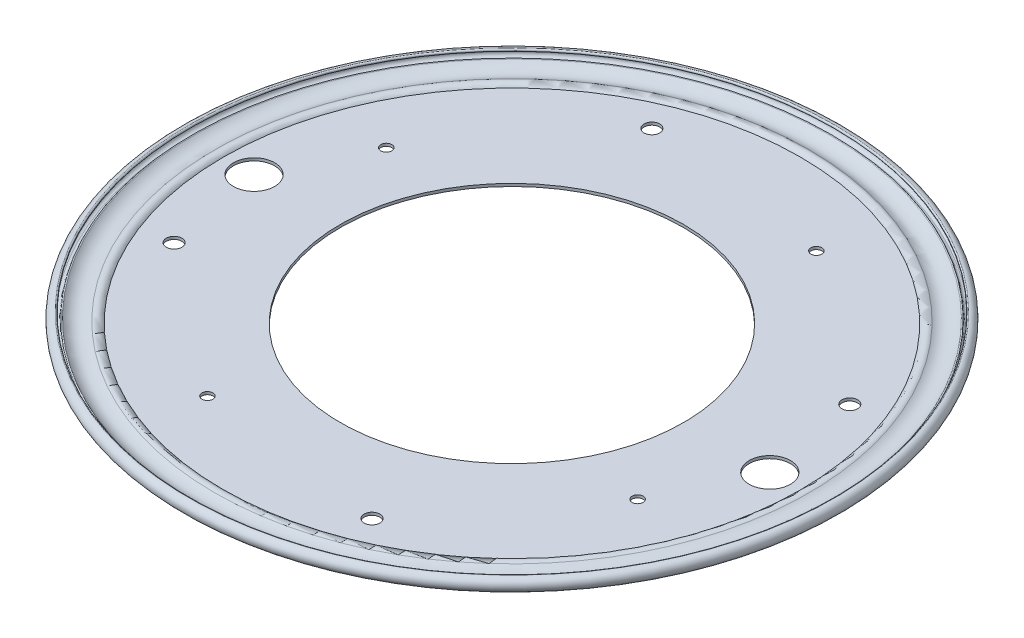
SolidWorks part; units mm, degrees
ref_plane "Front Plane" through (0, 0, 0) normal (0, 0, 1) x (1, 0, 0)
ref_plane "Top Plane" through (0, 0, 0) normal (0, 1, 0) x (1, 0, 0)
ref_plane "Right Plane" through (0, 0, 0) normal (1, 0, 0) x (0, 0, -1)
sketch "Sketch2" plane through (0, 0, 0) normal (1, 0, 0) x (0, 0, -1)
  line L0 (-151.13, 3.048) -> (-152.4, 3.048) construction
  line L1 (-149.352, 0) -> (-79.375, 0) construction
  line L3 (-149.352, 0) -> (-79.375, 0)
  line L4 (-79.375, 0) -> (-79.375, 1.27)
  line L5 (-79.375, 1.27) -> (-149.352, 1.27)
  line L7 (-79.375, 0) -> (-79.375, 1.27)
  line L9 (-146.9641, 4.445) -> (-134.3181, 4.445) construction
  line L10 (-79.375, 1.27) -> (-149.352, 1.27) construction
  line L11 (-133.35, 0) -> (-79.375, 0)
  line L12 (0, 0) -> (0, 11.2788) construction
  line L14 (-133.35, 1.27) -> (-133.35, 0) construction
  line L15 (-149.352, 1.27) -> (-146.9641, 3.2253) construction
  line L16 (-148.8469, 0.0421) -> (-146.9799, 1.5709) construction
  line L17 (-149.352, 3.048) -> (-148.4419, 1.5206) construction
  line L18 (-149.352, 3.048) -> (-147.5755, 3.1219) construction
  line L20 (-148.4419, 1.5206) -> (-147.8842, 0.5845) construction
  line L21 (-133.35, 1.27) -> (-79.375, 1.27)
  arc A0 (-146.9641, 5.6647) -> (-147.86, 3.2023) centre (-144.8759, 3.5108) ccw construction
  arc A1 (-137.3861, 6.7496) -> (-146.9641, 5.6647) centre (-141.472, 0) ccw construction
  arc A2 (-137.3861, 6.7496) -> (-133.35, 7.62) centre (-135.8289, 9.3219) ccw construction
  arc A3 (-149.352, 4.826) -> (-149.352, 1.27) centre (-149.352, 3.048) ccw
  arc A4 (-149.352, 4.826) -> (-149.352, 6.096) centre (-149.352, 5.461) ccw
  arc A5 (-149.352, 6.096) -> (-149.352, 0) centre (-149.352, 3.048) ccw
  arc A6 (-149.352, 4.826) -> (-149.352, 1.27) centre (-149.352, 3.048) ccw
  arc A8 (-149.352, 6.096) -> (-149.352, 0) centre (-149.352, 3.048) ccw
  arc A9 (-146.9641, 5.6647) -> (-147.86, 3.2023) centre (-144.8759, 3.5108) ccw construction
  arc A10 (-137.3861, 6.7496) -> (-146.9641, 5.6647) centre (-141.472, 0) ccw construction
  arc A11 (-137.3861, 6.7496) -> (-133.35, 7.62) centre (-135.8289, 9.3219) ccw construction
  arc A12 (-137.3861, 2.1404) -> (-146.9641, 3.2253) centre (-141.472, 8.89) cw
  arc A13 (-137.3861, 2.1404) -> (-133.35, 1.27) centre (-135.8289, -0.4319) cw
  arc A14 (-149.352, 6.096) -> (-148.8469, 0.0421) centre (-149.352, 3.048) ccw
  arc A15 (-136.7284, 1.054) -> (-146.9799, 1.5709) centre (-141.472, 8.89) cw
  arc A16 (-136.7284, 1.054) -> (-134.397, 0.5512) centre (-135.8289, -0.4319) cw
  arc A19 (-149.352, 6.096) -> (-149.352, 4.826) centre (-149.352, 5.461) cw
  arc A20 (-149.9719, 4.4139) -> (-147.86, 3.2023) centre (-149.352, 3.048) ccw construction
  spline S0 degree 3 poles (-149.352, 1.27) (-148.8075, 1.2737) (-148.0125, 1.6481) (-147.6196, 2.5655) (-147.6545, 3.1836) (-147.2533, 3.5057) (-146.9641, 3.2253) knots 0 0 0 0 0.465884 0.688178 0.820435 1 1 1 1
  spline S1 degree 3 poles (-148.8469, 0.0421) (-148.5477, 0.1455) (-147.9178, 0.3764) (-147.5362, 1.1846) (-147.3566, 1.6091) (-146.9799, 1.5709) knots 0 0 0 0 0.485698 0.694957 1 1 1 1
  spline S3 degree 2 poles (-134.397, 0.5512) (-133.999, 0.0551) (-133.35, 0) knots 0 0 0 1 1 1
  dimension "D2" = 1.778
  dimension "D5" = 1.2185
  dimension "D3" = 1.27
  dimension "D4" = 0.7677
  dimension "D6" = 0.6653
  dimension "D1" = 0
revolve "Revolve1" add sketch "Sketch2" angle 360 about L12
sketch "Sketch3" plane through (0, 1.27, 0) normal (0, 1, 0) x (1, 0, 0)
  circle A0 centre (110.4699, 45.7548) radius 3.6195 construction
  circle A1 centre (119.253, 0) radius 9.525 construction
  circle A2 centre (99.4445, -41.3427) radius 2.54 construction
  circle A3 centre (45.7548, -110.4699) radius 3.6195 construction
  circle A4 centre (-41.3427, -99.4445) radius 2.54 construction
  circle A5 centre (-110.4699, -45.7548) radius 3.6195 construction
  circle A6 centre (-119.253, 0) radius 9.525 construction
  circle A7 centre (-99.4445, 41.3427) radius 2.54 construction
  circle A8 centre (41.3427, 99.4445) radius 2.54 construction
  circle A9 centre (-45.7548, 110.4699) radius 3.6195 construction
  circle A10 centre (110.4699, 45.7548) radius 3.6195
  circle A11 centre (119.253, 0) radius 9.525
  circle A12 centre (99.4445, -41.3427) radius 2.54
  circle A13 centre (45.7548, -110.4699) radius 3.6195
  circle A14 centre (-41.3427, -99.4445) radius 2.54
  circle A15 centre (-110.4699, -45.7548) radius 3.6195
  circle A16 centre (-119.253, 0) radius 9.525
  circle A17 centre (-99.4445, 41.3427) radius 2.54
  circle A18 centre (41.3427, 99.4445) radius 2.54
  circle A19 centre (-45.7548, 110.4699) radius 3.6195
extrude "Cut-Extrude1" cut sketch "Sketch3" against normal up to surface (1.27 mm away)
